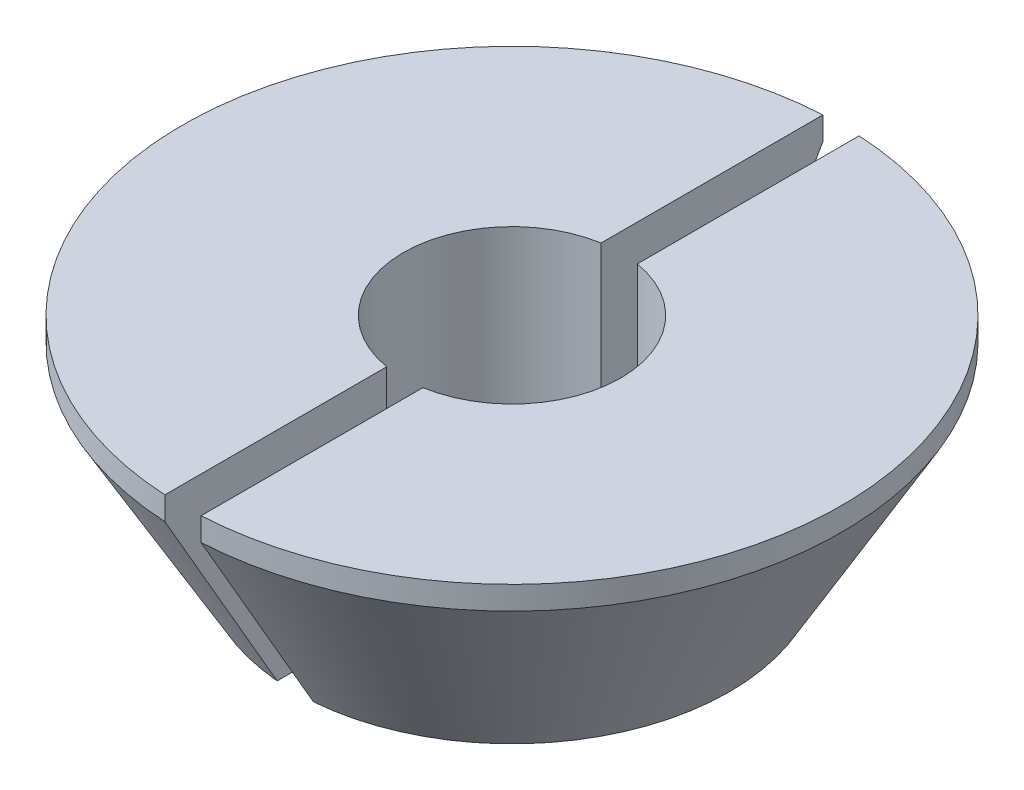
SolidWorks part; units mm, degrees
ref_plane "Plano frontal" through (0, 0, 0) normal (0, 0, 1) x (1, 0, 0)
ref_plane "Plano superior" through (0, 0, 0) normal (0, 1, 0) x (1, 0, 0)
ref_plane "Plano direito" through (0, 0, 0) normal (1, 0, 0) x (0, 0, -1)
sketch "Sketch1" plane through (0, 0, 0) normal (0, 0, 1) x (1, 0, 0)
  line L0 (0, 0) -> (0, 3.7048) construction
  line L1 (1.5, 0) -> (3, 0)
  line L2 (3, 0) -> (4.5473, 2.68)
  line L3 (4.5473, 2.68) -> (4.5473, 3)
  line L4 (4.5473, 3) -> (1.5, 3)
  line L5 (1.5, 3) -> (1.5, 0)
  dimension "D1" = 1.5
  dimension "D2" = 1.5
  dimension "D3" = 3
  dimension "D4" = 0.32
  dimension "D5" = 60
revolve "Revolve1" add sketch "Sketch1" angle 360 about L0
sketch "Sketch2" plane through (0, 3, 0) normal (0, 1, 0) x (1, 0, 0)
  line L1 (-0.25, 5) -> (0.25, 5)
  line L2 (-0.25, 5) -> (-0.25, -5)
  line L3 (-0.25, -5) -> (0.25, -5)
  line L4 (0.25, 5) -> (0.25, -5)
  line L5 (-0.25, 5) -> (0.25, -5) construction
  line L6 (-0.25, -5) -> (0.25, 5) construction
  point P0 (0, 0)
  point P6 (0.8386, -4.8411)
  dimension "D1" = 10
  dimension "D2" = 0.5
extrude "Cut-Extrude2" cut sketch "Sketch2" against normal blind 10
